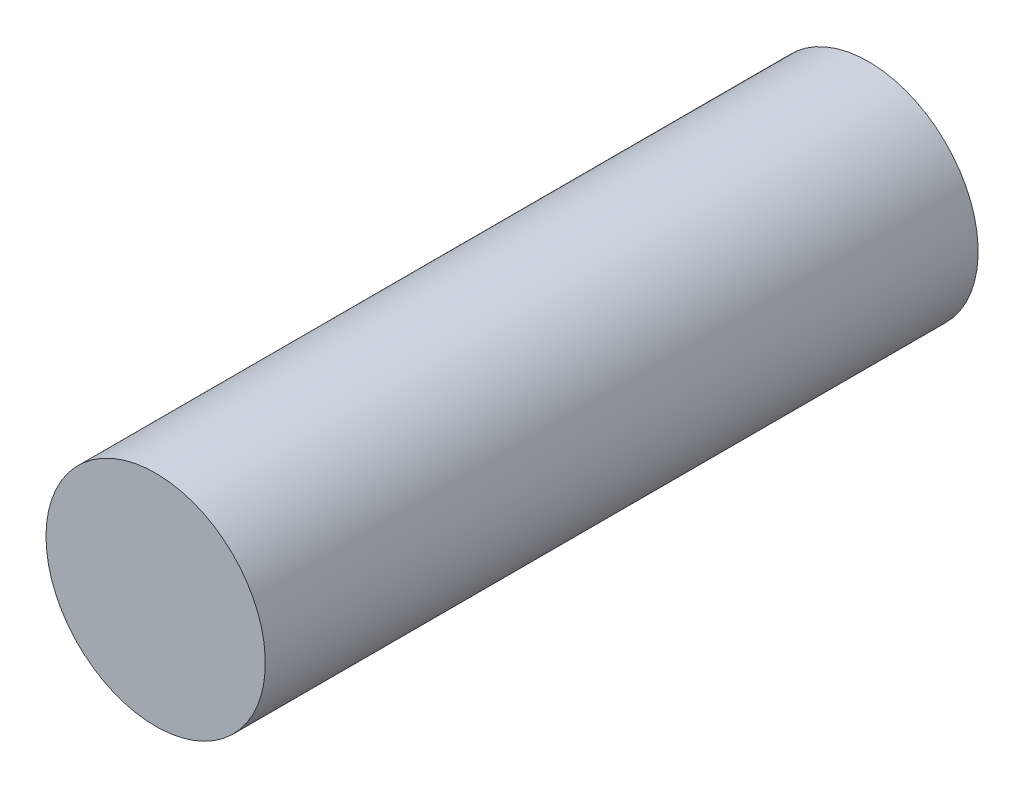
SolidWorks part; units mm, degrees
ref_plane "Piano frontale" through (0, 0, 0) normal (0, 0, 1) x (1, 0, 0)
ref_plane "Piano superiore" through (0, 0, 0) normal (0, 1, 0) x (1, 0, 0)
ref_plane "Piano destro" through (0, 0, 0) normal (1, 0, 0) x (0, 0, -1)
sketch "Schizzo1" plane through (0, 0, 0) normal (0, 0, 1) x (1, 0, 0)
  circle A0 centre (0, 0) radius 8
  dimension "D1" = 16
extrude "Estrusione-Estrusione1" add sketch "Schizzo1" along normal blind 52
cosmetic thread "Filettatura cosmetica1"
cosmetic thread "Filettatura cosmetica2"
